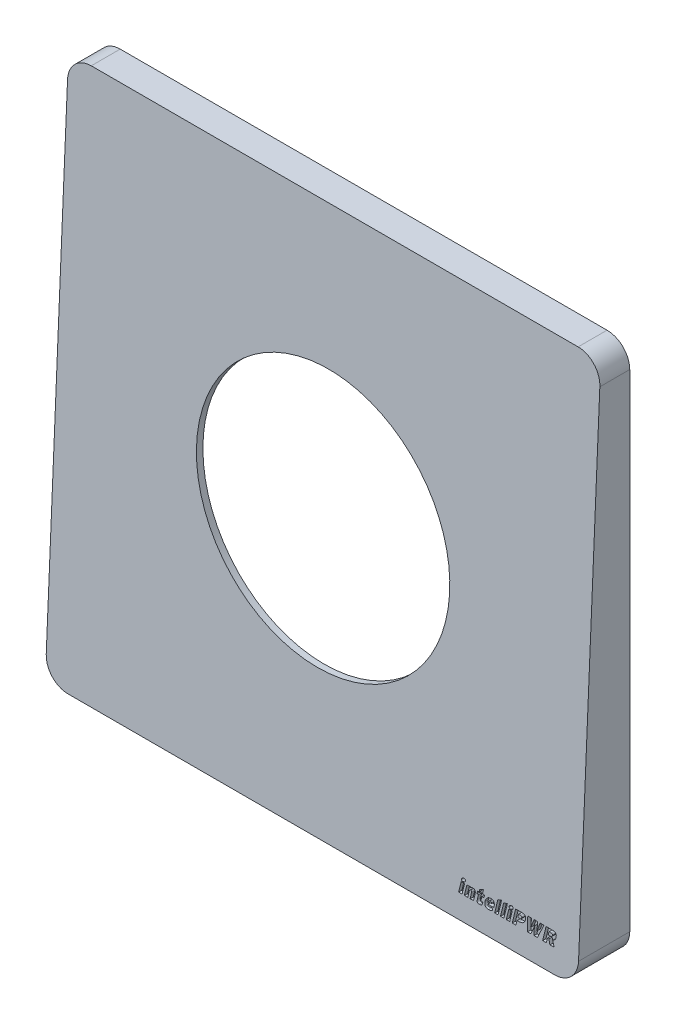
SolidWorks part; units mm, degrees
ref_plane "Front Plane" through (0, 0, 0) normal (0, 0, 1) x (1, 0, 0)
ref_plane "Top Plane" through (0, 0, 0) normal (0, 1, 0) x (1, 0, 0)
ref_plane "Right Plane" through (0, 0, 0) normal (1, 0, 0) x (0, 0, -1)
sketch "Sketch1" plane through (0, 0, 0) normal (0, 0, 1) x (1, 0, 0)
  line L0 (-38.566, 0) -> (72.4153, 0) construction
  line L1 (0, -49.5581) -> (0, 74.5126) construction
  line L2 (-37.5, 40) -> (37.5, 40)
  line L3 (-40, 37.5) -> (-40, -37.5)
  line L4 (-37.5, -40) -> (37.5, -40)
  line L5 (40, 37.5) -> (40, -37.5)
  arc A0 (-40, -37.5) -> (-37.5, -40) centre (-37.5, -37.5) ccw
  arc A1 (37.5, -40) -> (40, -37.5) centre (37.5, -37.5) ccw
  arc A2 (37.5, 40) -> (40, 37.5) centre (37.5, 37.5) cw
  arc A3 (-37.5, 40) -> (-40, 37.5) centre (-37.5, 37.5) ccw
  dimension "D3" = 2.5
  dimension "D1" = 80
  dimension "D2" = 80
  dimension "D4" = 40
  dimension "D5" = 40
extrude "Extrude-Thin1" add sketch "Sketch1" along normal blind 8 thin thin type one direction wall 1
sketch "Sketch5" plane through (41, 0, 0) normal (1, 0, 0) x (0, 0, -1)
  line L0 (20.3178, 0) -> (-25.0092, 0) construction
  line L1 (0, 43.59) -> (0, -45.2443) construction
  line L2 (-3.4562, 41) -> (-8, 41)
  line L3 (-8, 41) -> (-8, -41)
  line L4 (-8, -41) -> (-7.0437, -41)
  line L6 (-7.0437, -41) -> (-3.4562, 41)
  line L7 (-8, -41) -> (0, -41) construction
  line L11 (-8, 41) -> (0, 41) construction
extrude "Cut-Extrude2" cut sketch "Sketch5" against normal blind 120
sketch "Sketch6" plane through (41, 0, 0) normal (1, 0, 0) x (0, 0, -1)
  line L0 (-7.0437, -41) -> (-3.4562, 41)
  line L1 (-3.4562, 41) -> (-4.4572, 41)
  line L2 (-4.4572, 41) -> (-8.0447, -41)
  line L3 (-8.0447, -41) -> (-7.0437, -41)
  line L4 (-3.4562, 41) -> (-3.4562, 45.0301) construction
  dimension "D1" = 1
  dimension "D2" = 90
extrude "Boss-Extrude1" add sketch "Sketch6" against normal blind 82
sketch "Sketch7" plane through (0, 0, 0) normal (0, 0, -1) x (-1, 0, 0)
  line L0 (0, 0) -> (0, 69.537) construction
  line L1 (71.0569, 0) -> (20.5255, 0) construction
  line L2 (-37.5, 41) -> (37.5, 41)
  line L3 (-37.5, 41) -> (37.5, 41) construction
  line L4 (-41, -37.5) -> (-41, 37.5)
  line L5 (41, -37.5) -> (41, 37.5)
  line L6 (-41, -37.5) -> (-41, 37.5) construction
  line L7 (-37.5, -41) -> (37.5, -41)
  arc A0 (37.5, 41) -> (41, 37.5) centre (37.5, 37.5) cw
  arc A1 (-37.5, -41) -> (-41, -37.5) centre (-37.5, -37.5) cw
  arc A2 (37.5, -41) -> (41, -37.5) centre (37.5, -37.5) ccw
  arc A4 (-37.5, 41) -> (-41, 37.5) centre (-37.5, 37.5) ccw
  point P9 (0, -41)
  point P13 (-41, 0)
  point P14 (0, 41)
  point P25 (41, 0)
extrude "Cut-Extrude-Thin1" cut sketch "Sketch7" against normal blind 82 thin thin type one direction wall 11
sketch "Sketch8" plane through (0, 0.273, 6.239) normal (0, 0.0437, 0.999) x (1, 0, 0)
  line L0 (0, 0) -> (0, 28.9526) construction
  line L1 (23.1598, 0) -> (-27.4609, 0) construction
  circle A0 centre (0, 0) radius 19.5
  dimension "D1" = 39
extrude "Cut-Extrude3" cut sketch "Sketch8" against normal blind 82
sketch "Sketch9" plane through (0, 0.273, 6.239) normal (0, 0.0437, 0.999) x (1, 0, 0)
  line L1 (22.5318, -37.8124) -> (22.8563, -36.2774)
  line L3 (22.8563, -36.2774) -> (23.3824, -36.2774)
  line L4 (23.3824, -36.2774) -> (23.058, -37.8124)
  line L5 (23.058, -37.8124) -> (22.5318, -37.8124)
  line L6 (24.2906, -37.8124) -> (24.4746, -36.9301)
  line L7 (24.121, -36.9242) -> (23.9366, -37.8124)
  line L8 (23.9366, -37.8124) -> (23.4104, -37.8124)
  line L9 (23.4104, -37.8124) -> (23.7348, -36.2694)
  line L10 (23.7348, -36.2694) -> (24.261, -36.2694)
  line L11 (24.261, -36.2694) -> (24.2407, -36.3734)
  line L12 (25.0186, -36.8721) -> (24.8197, -37.8124)
  line L13 (24.8197, -37.8124) -> (24.2906, -37.8124)
  line L14 (25.3946, -37.3472) -> (25.5346, -36.6755)
  line L15 (25.5346, -36.6755) -> (25.3007, -36.6755)
  line L16 (25.3007, -36.6755) -> (25.3887, -36.2694)
  line L17 (25.3887, -36.2694) -> (25.6226, -36.2694)
  line L18 (25.6226, -36.2694) -> (25.7042, -35.8811)
  line L19 (25.7042, -35.8811) -> (26.2596, -35.6738)
  line L20 (26.2596, -35.6738) -> (26.134, -36.2694)
  line L21 (26.134, -36.2694) -> (26.4673, -36.2694)
  line L22 (26.4673, -36.2694) -> (26.3797, -36.6755)
  line L23 (26.3797, -36.6755) -> (26.0464, -36.6755)
  line L24 (26.0464, -36.6755) -> (25.9292, -37.2389)
  line L25 (26.2571, -37.3099) -> (26.0929, -37.7574)
  line L26 (27.0891, -36.865) -> (27.5277, -36.865)
  line L27 (27.9194, -37.1898) -> (27.0193, -37.1898)
  line L28 (27.6478, -37.3252) -> (27.7794, -37.6631)
  line L29 (28.0814, -37.8124) -> (28.4875, -35.8849)
  line L30 (28.4875, -35.8849) -> (29.0576, -35.6738)
  line L31 (29.0576, -35.6738) -> (28.6076, -37.8124)
  line L32 (28.6076, -37.8124) -> (28.0814, -37.8124)
  line L33 (28.9747, -37.8124) -> (29.3808, -35.8849)
  line L34 (29.3808, -35.8849) -> (29.951, -35.6738)
  line L35 (29.951, -35.6738) -> (29.5009, -37.8124)
  line L36 (29.5009, -37.8124) -> (28.9747, -37.8124)
  line L37 (29.8681, -37.8124) -> (30.1925, -36.2774)
  line L38 (30.1925, -36.2774) -> (30.7187, -36.2774)
  line L39 (30.7187, -36.2774) -> (30.3943, -37.8124)
  line L40 (30.3943, -37.8124) -> (29.8681, -37.8124)
  line L41 (31.9923, -36.2152) -> (31.6852, -36.2152)
  line L42 (31.6852, -36.2152) -> (31.5858, -36.6755)
  line L43 (31.5858, -36.6755) -> (31.884, -36.6755)
  line L44 (31.7728, -37.1357) -> (31.4894, -37.1357)
  line L45 (31.4894, -37.1357) -> (31.3489, -37.8124)
  line L46 (31.3489, -37.8124) -> (30.7906, -37.8124)
  line L47 (30.7906, -37.8124) -> (31.2233, -35.755)
  line L48 (31.2233, -35.755) -> (32.1031, -35.755)
  line L49 (34.6592, -37.8124) -> (34.1292, -37.8124)
  line L50 (34.1292, -37.8124) -> (34.1292, -37.3658)
  line L51 (33.8492, -37.3658) -> (33.6618, -37.8124)
  line L52 (33.6618, -37.8124) -> (33.1445, -37.8124)
  line L53 (33.1445, -37.8124) -> (33.0891, -35.755)
  line L54 (33.0891, -35.755) -> (33.6737, -35.755)
  line L55 (33.6737, -35.755) -> (33.6563, -36.0989)
  line L56 (33.9309, -36.1019) -> (34.0742, -35.755)
  line L57 (34.0742, -35.755) -> (34.6004, -35.755)
  line L58 (34.6004, -35.755) -> (34.5975, -36.1019)
  line L59 (34.8724, -36.0989) -> (35.001, -35.755)
  line L60 (35.001, -35.755) -> (35.5801, -35.755)
  line L61 (35.5801, -35.755) -> (34.6592, -37.8124)
  line L62 (36.7107, -36.2152) -> (36.3685, -36.2152)
  line L63 (36.3685, -36.2152) -> (36.2721, -36.6755)
  line L64 (36.2721, -36.6755) -> (36.6054, -36.6755)
  line L65 (36.5935, -37.8124) -> (36.4066, -37.1357)
  line L66 (36.4066, -37.1357) -> (36.1786, -37.1357)
  line L67 (36.1786, -37.1357) -> (36.0322, -37.8124)
  line L68 (36.0322, -37.8124) -> (35.4739, -37.8124)
  line L69 (35.4739, -37.8124) -> (35.9066, -35.755)
  line L70 (35.9066, -35.755) -> (36.8215, -35.755)
  line L71 (36.9823, -37.0278) -> (37.228, -37.8124)
  line L72 (37.228, -37.8124) -> (36.5935, -37.8124)
  spline S0 degree 3 poles (23.5051, -35.901) (23.4969, -35.9395) (23.475, -35.9951) (23.4259, -36.0567) (23.38, -36.0941) (23.3281, -36.1243) (23.2494, -36.1531) (23.1859, -36.1615) (23.1426, -36.1611) knots 0 0 0 0 0.243996 0.362518 0.483924 0.60781 0.732572 1 1 1 1
  spline S1 degree 3 poles (23.1426, -36.1611) (23.1034, -36.1614) (23.0464, -36.1543) (22.9794, -36.1247) (22.9459, -36.0992) (22.9246, -36.0749) (22.9109, -36.0553) (22.9015, -36.0333) (22.894, -36.0101) (22.8904, -35.985) (22.8893, -35.9483) (22.8933, -35.92) (22.8973, -35.901) knots 0 0 0 0 0.278361 0.398909 0.514848 0.572098 0.627439 0.683254 0.740687 0.799243 0.862128 1 1 1 1
  spline S2 degree 3 poles (22.8973, -35.901) (22.9046, -35.8648) (22.9269, -35.8129) (22.975, -35.7545) (23.0208, -35.7171) (23.0729, -35.6861) (23.1494, -35.6544) (23.2122, -35.6474) (23.2539, -35.6468) knots 0 0 0 0 0.233169 0.351346 0.477078 0.606225 0.734605 1 1 1 1
  spline S3 degree 3 poles (23.2539, -35.6468) (23.294, -35.6476) (23.3536, -35.6526) (23.4215, -35.6852) (23.4549, -35.7118) (23.4756, -35.7369) (23.4893, -35.7563) (23.4986, -35.7777) (23.5062, -35.8) (23.5103, -35.8237) (23.5118, -35.8577) (23.5094, -35.8837) (23.5051, -35.901) knots 0 0 0 0 0.289932 0.415109 0.533191 0.591068 0.646913 0.702321 0.757398 0.814668 0.873138 1 1 1 1
  spline S4 degree 3 poles (24.4746, -36.9301) (24.4788, -36.907) (24.4857, -36.8741) (24.4892, -36.8319) (24.4898, -36.805) (24.4882, -36.7812) (24.4845, -36.7603) (24.4788, -36.7423) (24.4679, -36.723) (24.4497, -36.7035) (24.4108, -36.6804) (24.3757, -36.6755) (24.3519, -36.6755) knots 0 0 0 0 0.206248 0.294568 0.372668 0.442258 0.50401 0.558886 0.607164 0.698385 0.78958 1 1 1 1
  spline S5 degree 3 poles (24.3519, -36.6755) (24.3255, -36.6748) (24.2865, -36.6813) (24.2396, -36.7028) (24.2139, -36.7214) (24.195, -36.7398) (24.1826, -36.7576) (24.1702, -36.7778) (24.159, -36.8014) (24.1478, -36.8274) (24.1346, -36.8686) (24.1258, -36.9012) (24.121, -36.9242) knots 0 0 0 0 0.211446 0.310999 0.411311 0.464021 0.521401 0.584742 0.653943 0.729878 0.812026 1 1 1 1
  spline S6 degree 3 poles (24.2407, -36.3734) (24.298, -36.3381) (24.3731, -36.2966) (24.4716, -36.2624) (24.5492, -36.2465) (24.6106, -36.2424) (24.6531, -36.2423) knots 0 0 0 0 0.460544 0.581348 0.71025 1 1 1 1
  spline S7 degree 3 poles (24.6531, -36.2423) (24.6921, -36.2424) (24.7488, -36.2462) (24.8195, -36.2639) (24.8654, -36.2813) (24.9061, -36.3046) (24.9414, -36.333) (24.9715, -36.3666) (24.9962, -36.4051) (25.0154, -36.4485) (25.031, -36.4959) (25.0401, -36.5481) (25.0459, -36.6044) (25.0457, -36.6652) (25.0409, -36.7555) (25.0276, -36.8247) (25.0186, -36.8721) knots 0 0 0 0 0.133988 0.193276 0.249258 0.301629 0.353161 0.403793 0.455519 0.509135 0.565969 0.625946 0.690505 0.759591 0.834116 1 1 1 1
  spline S8 degree 3 poles (26.0929, -37.7574) (26.0333, -37.7837) (25.9543, -37.8089) (25.856, -37.8278) (25.7854, -37.8368) (25.7316, -37.8398) (25.6953, -37.8395) knots 0 0 0 0 0.477931 0.605354 0.733676 1 1 1 1
  spline S9 degree 3 poles (25.6953, -37.8395) (25.6631, -37.8397) (25.6164, -37.8366) (25.5579, -37.8244) (25.5198, -37.8123) (25.4862, -37.7963) (25.457, -37.7764) (25.4315, -37.7536) (25.4109, -37.7263) (25.3947, -37.6948) (25.3825, -37.6588) (25.3741, -37.6184) (25.3701, -37.5731) (25.3704, -37.5232) (25.3757, -37.4469) (25.3864, -37.3879) (25.3946, -37.3472) knots 0 0 0 0 0.137072 0.197692 0.25376 0.30627 0.355446 0.403354 0.450795 0.500091 0.55332 0.611471 0.675246 0.745926 0.823384 1 1 1 1
  spline S10 degree 3 poles (25.9292, -37.2389) (25.9236, -37.2632) (25.9182, -37.2972) (25.9231, -37.3387) (25.9338, -37.3601) (25.9509, -37.3746) (25.9818, -37.3894) (26.0096, -37.391) (26.0286, -37.3916) knots 0 0 0 0 0.332431 0.451864 0.549009 0.641836 0.743993 1 1 1 1
  spline S11 degree 3 poles (26.0286, -37.3916) (26.0648, -37.392) (26.1102, -37.3818) (26.1624, -37.3596) (26.204, -37.3401) (26.2353, -37.3223) (26.2571, -37.3099) knots 0 0 0 0 0.439023 0.560347 0.693744 1 1 1 1
  spline S12 degree 3 poles (27.5277, -36.865) (27.5293, -36.8295) (27.529, -36.7789) (27.5142, -36.7178) (27.5009, -36.6876) (27.4872, -36.6673) (27.4736, -36.6552) (27.4583, -36.6443) (27.44, -36.6359) (27.4195, -36.6292) (27.3871, -36.6229) (27.3615, -36.621) (27.3437, -36.6213) knots 0 0 0 0 0.296749 0.416695 0.521302 0.57019 0.620056 0.671542 0.726187 0.786738 0.851475 1 1 1 1
  spline S13 degree 3 poles (27.3437, -36.6213) (27.3155, -36.6212) (27.2732, -36.6284) (27.2232, -36.6548) (27.1894, -36.682) (27.1587, -36.7168) (27.1208, -36.7764) (27.1008, -36.8283) (27.0891, -36.865) knots 0 0 0 0 0.222963 0.331063 0.443598 0.564297 0.695588 1 1 1 1
  spline S14 degree 3 poles (27.946, -37.0879) (27.9408, -37.1068) (27.9333, -37.1411) (27.9259, -37.1755) (27.9194, -37.1898) knots 0 0 0 0 0.556454 1 1 1 1
  spline S15 degree 3 poles (27.0193, -37.1898) (27.0159, -37.2265) (27.016, -37.2792) (27.0367, -37.342) (27.0613, -37.3767) (27.0938, -37.4024) (27.1478, -37.4284) (27.1948, -37.4328) (27.2265, -37.4334) knots 0 0 0 0 0.296056 0.414656 0.524028 0.631631 0.743271 1 1 1 1
  spline S16 degree 3 poles (27.2265, -37.4334) (27.2603, -37.4332) (27.3107, -37.4303) (27.3768, -37.4199) (27.4263, -37.4095) (27.477, -37.3938) (27.5522, -37.3685) (27.6086, -37.3424) (27.6478, -37.3252) knots 0 0 0 0 0.230948 0.344109 0.457558 0.576208 0.706686 1 1 1 1
  spline S17 degree 3 poles (27.7794, -37.6631) (27.7271, -37.6911) (27.6473, -37.7284) (27.5385, -37.7689) (27.4578, -37.7948) (27.3756, -37.8147) (27.2619, -37.8343) (27.1745, -37.8392) (27.1157, -37.8395) knots 0 0 0 0 0.256454 0.380104 0.501569 0.622664 0.745735 1 1 1 1
  spline S18 degree 3 poles (27.1157, -37.8395) (27.0622, -37.8393) (26.9842, -37.8333) (26.8864, -37.8083) (26.822, -37.7829) (26.7641, -37.7507) (26.7129, -37.7122) (26.6679, -37.6684) (26.6299, -37.6183) (26.5991, -37.5624) (26.5744, -37.5016) (26.5568, -37.4353) (26.5454, -37.3642) (26.541, -37.2886) (26.5441, -37.1801) (26.5568, -37.0976) (26.5688, -37.0422) knots 0 0 0 0 0.139839 0.202933 0.262718 0.320042 0.375234 0.429353 0.483442 0.538621 0.595401 0.654489 0.717096 0.783083 0.851913 1 1 1 1
  spline S19 degree 3 poles (26.5688, -37.0422) (26.5831, -36.9792) (26.6085, -36.8876) (26.6551, -36.7729) (26.6947, -36.6953) (26.7382, -36.6235) (26.786, -36.5578) (26.8379, -36.4981) (26.8939, -36.4448) (26.9531, -36.3973) (27.0154, -36.3562) (27.0807, -36.3212) (27.1487, -36.2925) (27.2191, -36.2701) (27.3158, -36.2482) (27.3903, -36.2428) (27.4401, -36.2423) knots 0 0 0 0 0.150666 0.221012 0.288513 0.353593 0.416668 0.477731 0.537737 0.596692 0.654605 0.711686 0.769156 0.826457 0.883737 1 1 1 1
  spline S20 degree 3 poles (27.4401, -36.2423) (27.4892, -36.2427) (27.5612, -36.2476) (27.6515, -36.2705) (27.712, -36.293) (27.7667, -36.323) (27.816, -36.3594) (27.8597, -36.4023) (27.8978, -36.4519) (27.9292, -36.5083) (27.954, -36.5714) (27.9704, -36.6415) (27.9806, -36.718) (27.9827, -36.8011) (27.9759, -36.9259) (27.96, -37.022) (27.946, -37.0879) knots 0 0 0 0 0.125235 0.182282 0.236835 0.289224 0.340575 0.392377 0.44488 0.49922 0.556302 0.616919 0.682128 0.752543 0.828415 1 1 1 1
  spline S21 degree 3 poles (30.8414, -35.901) (30.8332, -35.9395) (30.8113, -35.9951) (30.7621, -36.0567) (30.7163, -36.0941) (30.6643, -36.1243) (30.5857, -36.1531) (30.5221, -36.1615) (30.4789, -36.1611) knots 0 0 0 0 0.243996 0.362518 0.483924 0.60781 0.732572 1 1 1 1
  spline S22 degree 3 poles (30.4789, -36.1611) (30.4396, -36.1614) (30.3826, -36.1543) (30.3156, -36.1247) (30.2822, -36.0992) (30.2609, -36.0749) (30.2472, -36.0553) (30.2378, -36.0333) (30.2303, -36.0101) (30.2266, -35.985) (30.2256, -35.9483) (30.2295, -35.92) (30.2335, -35.901) knots 0 0 0 0 0.278361 0.398909 0.514848 0.572098 0.627439 0.683254 0.740687 0.799243 0.862128 1 1 1 1
  spline S23 degree 3 poles (30.2335, -35.901) (30.2409, -35.8648) (30.2632, -35.8129) (30.3113, -35.7545) (30.3571, -35.7171) (30.4091, -35.6861) (30.4857, -35.6544) (30.5484, -35.6474) (30.5901, -35.6468) knots 0 0 0 0 0.233169 0.351346 0.477078 0.606225 0.734605 1 1 1 1
  spline S24 degree 3 poles (30.5901, -35.6468) (30.6303, -35.6476) (30.6899, -35.6526) (30.7578, -35.6852) (30.7912, -35.7118) (30.8118, -35.7369) (30.8255, -35.7563) (30.8349, -35.7777) (30.8425, -35.8) (30.8465, -35.8237) (30.8481, -35.8577) (30.8456, -35.8837) (30.8414, -35.901) knots 0 0 0 0 0.289932 0.415109 0.533191 0.591068 0.646913 0.702321 0.757398 0.814668 0.873138 1 1 1 1
  spline S25 degree 3 poles (32.1911, -36.4411) (32.1981, -36.411) (32.2031, -36.3661) (32.1907, -36.3103) (32.176, -36.2817) (32.16, -36.2619) (32.1446, -36.2493) (32.1264, -36.2386) (32.1054, -36.2297) (32.081, -36.2237) (32.0434, -36.2164) (32.0132, -36.2152) (31.9923, -36.2152) knots 0 0 0 0 0.254138 0.360693 0.463314 0.514097 0.568127 0.624482 0.687009 0.753851 0.828928 1 1 1 1
  spline S26 degree 3 poles (31.884, -36.6755) (31.9253, -36.6752) (31.9847, -36.6702) (32.0552, -36.6447) (32.0969, -36.6188) (32.1302, -36.5843) (32.1679, -36.5274) (32.184, -36.4765) (32.1911, -36.4411) knots 0 0 0 0 0.29062 0.412092 0.523259 0.631698 0.74585 1 1 1 1
  spline S27 degree 3 poles (32.7583, -36.4322) (32.745, -36.4934) (32.7207, -36.5823) (32.6705, -36.6906) (32.6282, -36.7622) (32.5799, -36.8261) (32.5278, -36.8845) (32.4699, -36.9355) (32.4079, -36.9809) (32.3411, -37.0191) (32.2706, -37.0524) (32.1959, -37.0794) (32.1174, -37.1003) (32.0356, -37.1165) (31.9205, -37.1307) (31.8324, -37.1365) (31.7728, -37.1357) knots 0 0 0 0 0.141358 0.206507 0.268664 0.328624 0.386922 0.444795 0.502156 0.559848 0.618159 0.677698 0.738624 0.801161 0.865596 1 1 1 1
  spline S28 degree 3 poles (32.1031, -35.755) (32.1595, -35.7545) (32.242, -35.7594) (32.3481, -35.7746) (32.4205, -35.7906) (32.4878, -35.8108) (32.5484, -35.8376) (32.6029, -35.8692) (32.6503, -35.9073) (32.6911, -35.9508) (32.7246, -36.0007) (32.7504, -36.057) (32.7685, -36.1196) (32.7791, -36.1885) (32.7814, -36.2941) (32.7698, -36.3761) (32.7583, -36.4322) knots 0 0 0 0 0.148313 0.216935 0.281917 0.343283 0.401251 0.455966 0.508744 0.560452 0.612308 0.666251 0.722712 0.783153 0.849211 1 1 1 1
  spline S29 degree 3 poles (34.1292, -37.3658) (34.1269, -37.284) (34.1283, -37.1605) (34.1355, -36.9976) (34.1408, -36.8793) (34.1467, -36.7691) (34.1519, -36.6833) (34.1555, -36.6211) (34.1605, -36.5706) (34.1642, -36.5352) (34.1677, -36.5134) knots 0 0 0 0 0.287418 0.433707 0.573086 0.703583 0.821712 0.874842 0.922617 1 1 1 1
  spline S30 degree 3 poles (34.1677, -36.5134) (34.1615, -36.5355) (34.1493, -36.5706) (34.134, -36.6213) (34.119, -36.6661) (34.1033, -36.7149) (34.0853, -36.7666) (34.0661, -36.821) (34.0373, -36.8977) (33.9988, -36.9979) (33.9339, -37.161) (33.8835, -37.2843) (33.8492, -37.3658) knots 0 0 0 0 0.075538 0.122272 0.174583 0.231301 0.291254 0.354892 0.421349 0.561229 0.70869 1 1 1 1
  spline S31 degree 3 poles (33.6563, -36.0989) (33.6542, -36.175) (33.6483, -36.2905) (33.6383, -36.4452) (33.6297, -36.5627) (33.6213, -36.6781) (33.6078, -36.821) (33.5985, -36.9253) (33.5916, -36.9923) knots 0 0 0 0 0.254779 0.387257 0.519329 0.649082 0.774717 1 1 1 1
  spline S32 degree 3 poles (33.5916, -36.9923) (33.6117, -36.9251) (33.6463, -36.8211) (33.6993, -36.6803) (33.744, -36.5665) (33.7913, -36.4507) (33.852, -36.2948) (33.8989, -36.1785) (33.9309, -36.1019) knots 0 0 0 0 0.22063 0.344767 0.473491 0.605508 0.738598 1 1 1 1
  spline S33 degree 3 poles (34.5975, -36.1019) (34.5952, -36.1789) (34.5937, -36.2952) (34.5917, -36.4504) (34.5893, -36.5668) (34.5853, -36.6807) (34.577, -36.8224) (34.5688, -36.9258) (34.5624, -36.9923) knots 0 0 0 0 0.259139 0.391547 0.522548 0.65076 0.77529 1 1 1 1
  spline S34 degree 3 poles (34.5624, -36.9923) (34.5824, -36.925) (34.6152, -36.8204) (34.6635, -36.6779) (34.7028, -36.5624) (34.745, -36.445) (34.8026, -36.2905) (34.8461, -36.1755) (34.8724, -36.0989) knots 0 0 0 0 0.222644 0.347664 0.477214 0.609762 0.743344 1 1 1 1
  spline S35 degree 3 poles (36.9121, -36.4407) (36.9178, -36.4114) (36.9227, -36.367) (36.9079, -36.3124) (36.8932, -36.2833) (36.8767, -36.2633) (36.8615, -36.25) (36.8427, -36.2398) (36.822, -36.23) (36.7979, -36.2237) (36.7609, -36.2165) (36.7312, -36.2152) (36.7107, -36.2152) knots 0 0 0 0 0.248425 0.356514 0.461365 0.51411 0.56924 0.626959 0.689289 0.756874 0.831295 1 1 1 1
  spline S36 degree 3 poles (36.6054, -36.6755) (36.6467, -36.6753) (36.706, -36.6701) (36.7764, -36.6438) (36.8177, -36.617) (36.8513, -36.5826) (36.8886, -36.5258) (36.9046, -36.4756) (36.9121, -36.4407) knots 0 0 0 0 0.291424 0.412585 0.525066 0.635143 0.748168 1 1 1 1
  spline S37 degree 3 poles (36.8215, -35.755) (36.8779, -35.7545) (36.9604, -35.7593) (37.0665, -35.7746) (37.139, -35.7905) (37.206, -35.8114) (37.2669, -35.8375) (37.3212, -35.8693) (37.3687, -35.907) (37.41, -35.9497) (37.4431, -35.9994) (37.4698, -36.0545) (37.4882, -36.1161) (37.4992, -36.1841) (37.5021, -36.2884) (37.4911, -36.3696) (37.4793, -36.425) knots 0 0 0 0 0.149106 0.218094 0.283424 0.345229 0.403358 0.458364 0.511193 0.563161 0.614984 0.668363 0.724518 0.784604 0.849908 1 1 1 1
  spline S38 degree 3 poles (37.4793, -36.425) (37.4711, -36.4624) (37.4574, -36.5173) (37.4311, -36.5868) (37.4103, -36.6359) (37.3866, -36.6821) (37.36, -36.7255) (37.3315, -36.7666) (37.2897, -36.8171) (37.2324, -36.8747) (37.1299, -36.9558) (37.0433, -37.0031) (36.9823, -37.0278) knots 0 0 0 0 0.140675 0.207617 0.273118 0.336662 0.398558 0.459984 0.520403 0.639569 0.758048 1 1 1 1
extrude "Cut-Extrude13" cut sketch "Sketch9" against normal blind 0.5
